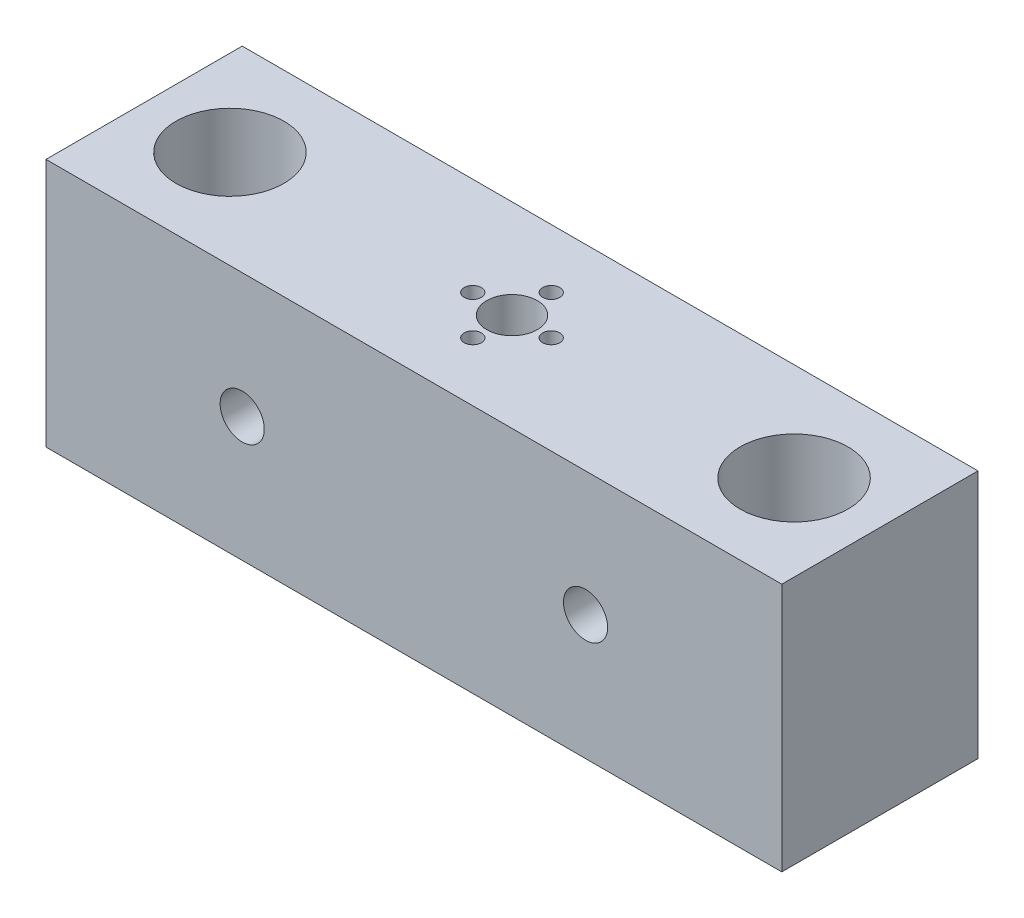
SolidWorks part; units mm, degrees
material "Liga 1060"
ref_plane "Frontal" through (0, 0, 0) normal (0, 0, 1) x (1, 0, 0)
ref_plane "Superior" through (0, 0, 0) normal (0, 1, 0) x (1, 0, 0)
ref_plane "Direito" through (0, 0, 0) normal (1, 0, 0) x (0, 0, -1)
sketch "Esboço1" plane through (0, 0, 0) normal (0, 1, 0) x (1, 0, 0)
  line L1 (-75, 20) -> (75, 20)
  line L2 (-75, 20) -> (-75, -20)
  line L3 (-75, -20) -> (75, -20)
  line L4 (75, 20) -> (75, -20)
  line L5 (-75, 20) -> (75, -20) construction
  line L6 (-75, -20) -> (75, 20) construction
  point P0 (0, 0)
  dimension "D1" = 150
  dimension "D2" = 40
extrude "Ressalto-extrusão1" add sketch "Esboço1" along normal blind 50.8
sketch "Esboço2" plane through (0, 50.8, 0) normal (0, 1, 0) x (1, 0, 0)
  line L0 (-75, 20) -> (-75, -20) construction
  line L2 (75, 20) -> (-75, 20) construction
  line L3 (75, -20) -> (75, 20) construction
  circle A0 centre (0, 0) radius 5.15
  circle A1 centre (-57.5, 0) radius 11
  circle A2 centre (57.5, 0) radius 11
  dimension "D1" = 22
  dimension "D2" = 22
  dimension "D3" = 10.3
  dimension "D4" = 17.5
  dimension "D5" = 17.5
  dimension "D6" = 20
  dimension "D7" = 20
extrude "Corte-extrusão1" cut sketch "Esboço2" against normal through all
sketch "Esboço3" plane through (0, 50.8, 0) normal (0, 1, 0) x (1, 0, 0)
  circle A0 centre (0, 0) radius 8
  circle A1 centre (0, 8) radius 1.75
  dimension "D1" = 3.5
extrude "Corte-extrusão2" cut sketch "Esboço3" against normal through all contours A0 A1 | A0 A1
pattern_circular "PadrãoCircular1" count 4 over 360 about axis through (0, 0, 0) along (0, 1, 0) of "Corte-extrusão2"
sketch "Esboço5" plane through (0, 0, -20) normal (0, 0, -1) x (-1, 0, 0)
  line L0 (-35, 25.4) -> (35, 25.4) construction
  line L1 (75, 50.8) -> (75, 0) construction
  line L2 (-75, 50.8) -> (-75, 0) construction
  line L4 (-75, 25.4) -> (75, 25.4) construction
  circle A0 centre (35, 25.4) radius 4
  circle A1 centre (-35, 25.4) radius 4
  dimension "D3" = 8
  dimension "D1" = 40
  dimension "D2" = 40
extrude "Corte-extrusão3" cut sketch "Esboço5" against normal through all
hole_wizard "Furo roscado de M10x1.01" positions "Esboço6" profile "Esboço7" tap size "M10x1.0" standard "ISO" end condition through all
sketch "Esboço6" plane through (0, 0, -20) normal (0, 0, -1) x (-1, 0, 0)
  point P0 (35, 25.4)
  point P3 (-35, 25.4)
sketch "Esboço7" plane through (-35, 25.4, -20) normal (1, 0, 0) x (0, 1, 0)
  line L0 (0, 0) -> (0, 40)
  line L1 (0, 40) -> (4.5, 40)
  line L2 (4.5, 40) -> (4.5, 0.525)
  line L3 (4.5, 0.525) -> (5.025, 0)
  line L5 (5.025, 0) -> (0, 0)
  line L6 (-4.5, 0.525) -> (-5.025, 0) construction
  line L11 (0, -6.35) -> (0, 107.95) construction
  dimension "Thru Tap Drill Dia." = 9
  dimension "Thru Tap Drill Depth" = 40
  dimension "Near C'Sink Dia." = 10.05
  dimension "Near C'Sink Angle" = 90
cosmetic thread "Rosca de furo1" parameters "D2"=10
cosmetic thread "Rosca de furo2" parameters "D2"=10
